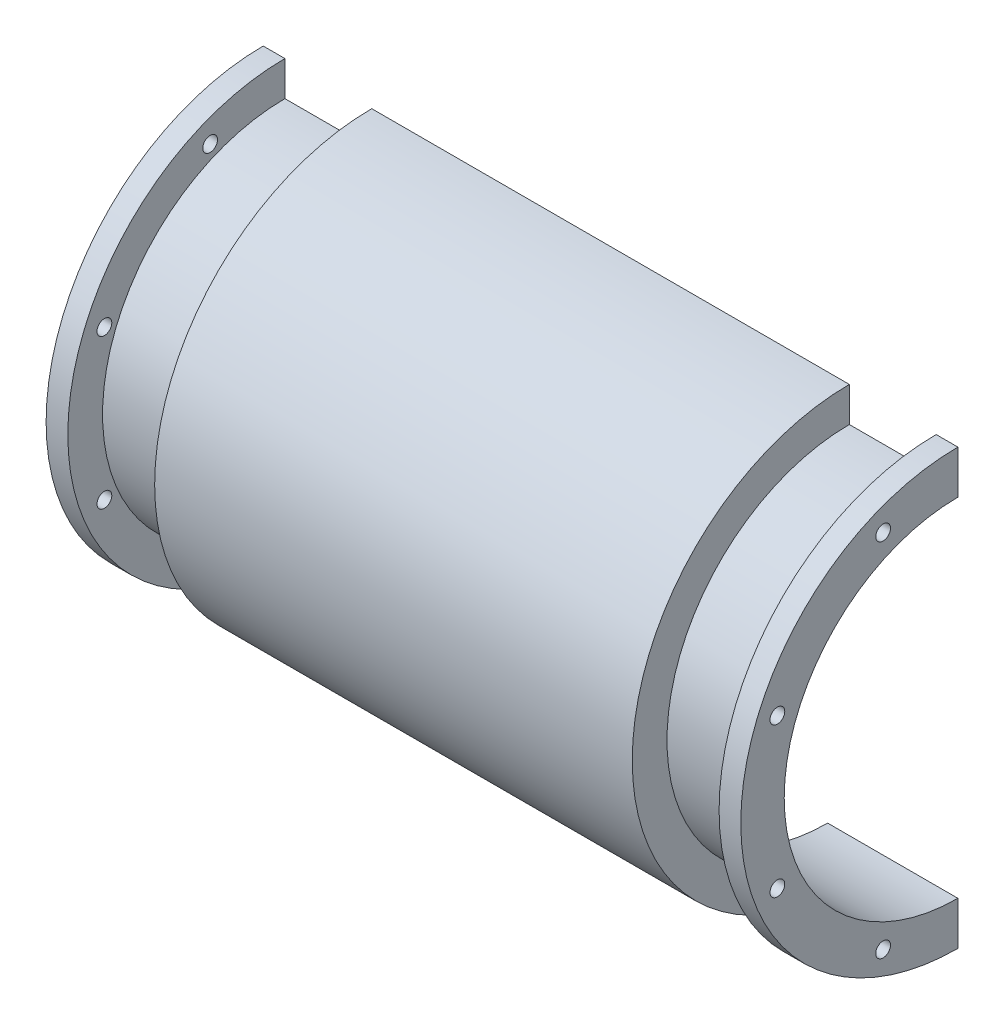
SolidWorks part; units mm, degrees
ref_plane "正面" through (0, 0, 0) normal (0, 0, 1) x (1, 0, 0)
ref_plane "平面" through (0, 0, 0) normal (0, 1, 0) x (1, 0, 0)
ref_plane "右側面" through (0, 0, 0) normal (1, 0, 0) x (0, 0, -1)
sketch "ｽｹｯﾁ1" plane through (0, 0, 0) normal (0, 0, 1) x (1, 0, 0)
  line L0 (-80, 40) -> (-50, 40)
  line L1 (-50, 40) -> (-50, 49)
  line L2 (-50, 49) -> (50, 49)
  line L3 (50, 49) -> (50, 40)
  line L4 (50, 40) -> (80, 40)
  line L5 (80, 40) -> (80, 50)
  line L6 (80, 50) -> (75, 50)
  line L7 (75, 50) -> (75, 42)
  line L8 (75, 42) -> (55, 42)
  line L9 (55, 42) -> (55, 50)
  line L10 (55, 50) -> (-55, 50)
  line L11 (-55, 50) -> (-55, 42)
  line L12 (-55, 42) -> (-75, 42)
  line L13 (-75, 42) -> (-75, 50)
  line L14 (-75, 50) -> (-80, 50)
  line L15 (-80, 50) -> (-80, 40)
  point P3 (0, 49)
  point P18 (0, 50)
  dimension "D1" = 1
  dimension "D2" = 10
  dimension "D3" = 2
  dimension "D4" = 160
  dimension "D5" = 5
  dimension "D6" = 5
  dimension "D7" = 20
  dimension "D8" = 50
sketch "ｽｹｯﾁ2" plane through (0, 0, 0) normal (0, 0, 1) x (1, 0, 0)
  line L0 (-50, 0) -> (50, 0)
  point P3 (0, 0)
  dimension "D1" = 100
revolve "回転1" add sketch "ｽｹｯﾁ1" angle 180 about L0
hole_wizard "M3 すきま穴1" positions "ｽｹｯﾁ5" profile "ｽｹｯﾁ6" hole size "M3" standard "JIS"
sketch "ｽｹｯﾁ5" plane through (-80, 0, 0) normal (-1, 0, 0) x (0, 0, 1)
  line L5 (0, 0) -> (17.2208, -41.5746)
  line L7 (0, -50) -> (0, -40) construction
  circle A0 centre (0, 0) radius 40 construction
  point P0 (17.2208, -41.5746)
  dimension "D1" = 45
  dimension "D2" = 22.5
sketch "ｽｹｯﾁ6" plane through (-80, -41.5746, 17.2208) normal (0, 1, 0) x (0, 0, 1)
  line L0 (0, 0) -> (0, 5)
  line L1 (0, 5) -> (1.7, 5)
  line L2 (1.7, 5) -> (1.7, 0)
  line L5 (1.7, 0) -> (0, 0)
  line L11 (0, -6.35) -> (0, 107.95) construction
  dimension "通し穴の直径" = 3.4
  dimension "通し穴の深さ" = 5
pattern_circular "円形ﾊﾟﾀｰﾝ1" count 4 every 45 about axis through (0, 0, 0) along (1, 0, 0) of "M3 すきま穴1"
mirror "ﾐﾗｰ1" about plane through (0, 0, 0) normal (1, 0, 0) of "円形ﾊﾟﾀｰﾝ1", "M3 すきま穴1"
